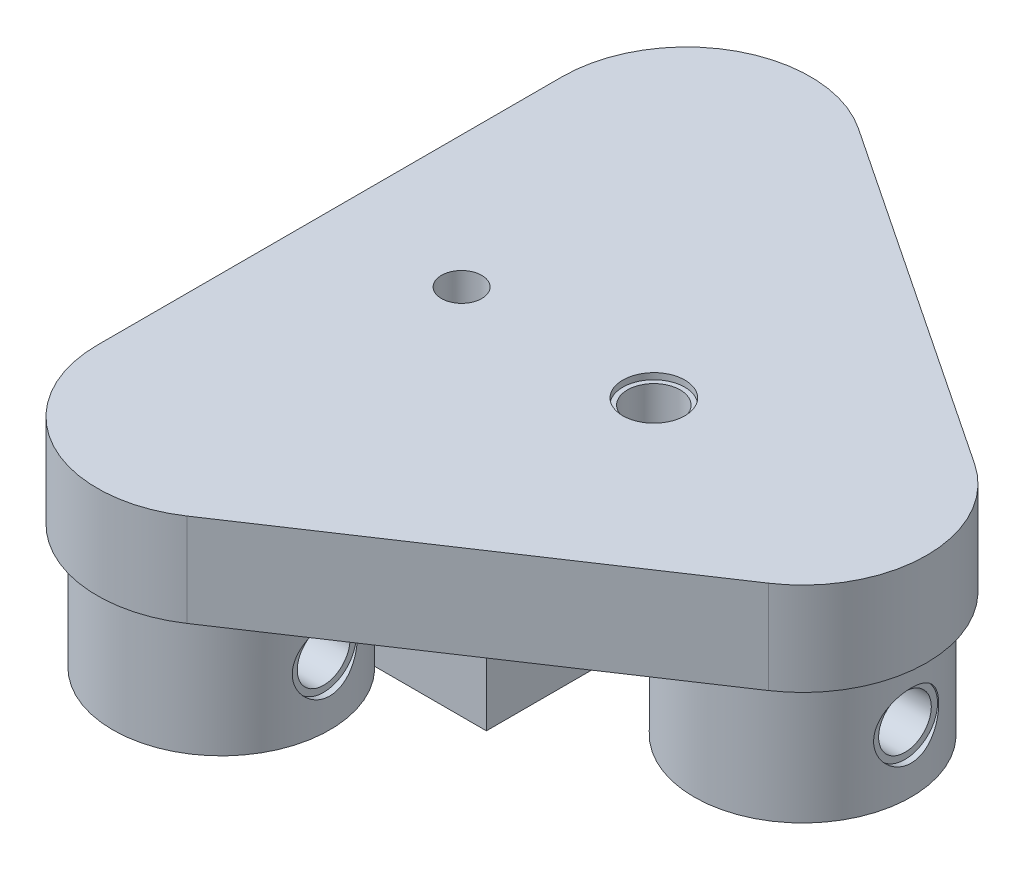
SolidWorks part; units mm, degrees
ref_plane "Front Plane" through (0, 0, 0) normal (0, 0, 1) x (1, 0, 0)
ref_plane "Top Plane" through (0, 0, 0) normal (0, 1, 0) x (1, 0, 0)
ref_plane "Right Plane" through (0, 0, 0) normal (1, 0, 0) x (0, 0, -1)
sketch "Sketch1" plane through (0, 0, 0) normal (0, 1, 0) x (1, 0, 0)
  line L0 (-28.125, 18.75) -> (0, 0) construction
  line L1 (0, 0) -> (-28.125, -18.75) construction
  line L2 (-38.125, 18.75) -> (-38.125, -18.75)
  line L3 (-22.578, -27.0705) -> (5.547, -8.3205)
  line L4 (5.547, 8.3205) -> (-22.578, 27.0705)
  circle A0 centre (0, 0) radius 5 construction
  circle A1 centre (-28.125, 18.75) radius 5 construction
  circle A2 centre (-28.125, -18.75) radius 5 construction
  arc A3 (-22.578, 27.0705) -> (-38.125, 18.75) centre (-28.125, 18.75) ccw
  arc A4 (5.547, -8.3205) -> (5.547, 8.3205) centre (0, 0) ccw
  arc A5 (-38.125, -18.75) -> (-22.578, -27.0705) centre (-28.125, -18.75) ccw
  dimension "D1" = 10
  dimension "D3" = 5
  dimension "D4" = 5
  dimension "D2" = 37.5
  dimension "D5" = 28.125
extrude "Boss-Extrude1" add sketch "Sketch1" along normal blind 7.5
sketch "Sketch3" plane through (0, 0, 0) normal (0, -1, 0) x (1, 0, 0)
  circle A0 centre (-28.125, 18.75) radius 5.125
  circle A1 centre (0, 0) radius 5.125
  circle A2 centre (-28.125, -18.75) radius 5.125
  circle A3 centre (-28.125, 18.75) radius 8.75
  circle A4 centre (-28.125, -18.75) radius 8.75
  circle A5 centre (0, 0) radius 8.75
  dimension "D1" = 10.25
  dimension "D2" = 17.5
sketch "Sketch6" plane through (0, 0, 0) normal (0, -1, 0) x (1, 0, 0)
  line L1 (-18, -7.5) -> (-37, -7.5)
  line L2 (-18, -7.5) -> (-18, 7.5)
  line L3 (-18, 7.5) -> (-37, 7.5)
  line L4 (-37, -7.5) -> (-37, 7.5)
  line L5 (-18, -7.5) -> (-37, 7.5) construction
  line L6 (-18, 7.5) -> (-37, -7.5) construction
  line L7 (-35, -5.5) -> (-35, 5.5)
  line L8 (-20, 5.5) -> (-35, 5.5)
  line L9 (-20, -5.5) -> (-20, 5.5)
  line L10 (-20, -5.5) -> (-35, -5.5)
  point P0 (-27.5, 0)
  dimension "D1" = 27.5
  dimension "D2" = 15
  dimension "D3" = 11
  dimension "D5" = 11
  dimension "D4" = 2
extrude "Boss-Extrude3" add sketch "Sketch6" along normal blind 15
sketch "Sketch7" plane through (0, 0, 0) normal (0, -1, 0) x (1, 0, 0)
  point P0 (-27.5, 0)
hole_wizard "M3 Clearance Hole1" positions "Sketch7" profile "Sketch8" hole size "M3" standard "ANSI Metric" end condition through all
sketch "Sketch8" plane through (-27.5, 0, 0) normal (1, 0, 0) x (0, 0, -1)
  line L0 (0, 0) -> (0, 7.5)
  line L1 (0, 7.5) -> (1.625, 7.5)
  line L2 (1.625, 7.5) -> (1.625, 0)
  line L5 (1.625, 0) -> (0, 0)
  line L11 (0, -6.35) -> (0, 107.95) construction
  dimension "Thru Hole Dia." = 3.25
  dimension "Thru Hole Depth" = 7.5
sketch "Sketch9" plane through (0, 7.5, 0) normal (0, 1, 0) x (1, 0, 0)
  point P0 (-12, 0)
  dimension "D1" = 12
hole_wizard "CBORE for M5 Hex Head Machine Screw1" positions "Sketch9" profile "Sketch10" counterbore size "M5" standard "ANSI Metric" end condition through all
sketch "Sketch10" plane through (-12, 7.5, 0) normal (1, 0, 0) x (0, 0, 1)
  line L0 (0, 0) -> (0, 22.5)
  line L1 (0, 22.5) -> (2.125, 22.5)
  line L3 (2.125, 22.5) -> (2.125, 0.5)
  line L4 (2.125, 0.5) -> (2.5, 0.5)
  line L5 (2.5, 0.5) -> (2.5, 0)
  line L7 (2.5, 0) -> (0, 0)
  line L11 (0, -6.35) -> (0, 107.95) construction
  dimension "Thru Hole Dia." = 4.25
  dimension "Thru Hole Depth" = 22.5
  dimension "C'Bore Dia." = 5
  dimension "C'Bore Depth" = 0.5
extrude "Boss-Extrude4" add sketch "Sketch3" along normal blind 10
ref_plane "Plane1" through (-19.375, 0, 0) normal (1, 0, 0) x (0, 0, -1)
sketch "Sketch11" plane through (-19.375, 0, 0) normal (1, 0, 0) x (0, 0, -1)
  line L0 (-18.75, -10) -> (-18.75, 0) construction
  line L1 (-27.5, -10) -> (-10, -10) construction
  line L2 (-27.0705, 0) -> (-8.3205, 0) construction
  line L3 (18.75, -10) -> (18.75, 0) construction
  line L4 (10, -10) -> (27.5, -10) construction
  line L5 (8.3205, 0) -> (27.0705, 0) construction
  point P12 (18.75, -5)
  point P13 (-18.75, -5)
hole_wizard "CBORE for M3 SHCS1" positions "Sketch11" profile "Sketch12" counterbore size "M3" standard "ANSI Metric"
sketch "Sketch12" plane through (-19.375, -5, 18.75) normal (0, 1, 0) x (0, 0, -1)
  line L0 (0, 0) -> (0, 10)
  line L1 (0, 10) -> (2.125, 10)
  line L2 (2.125, 10) -> (2.125, 0.5)
  line L3 (2.125, 0.5) -> (2.625, 0.5)
  line L4 (2.625, 0.5) -> (2.625, 0)
  line L5 (2.625, 0) -> (0, 0)
  line L10 (0, 10) -> (-2.125, 10) construction
  line L11 (0, -6.35) -> (0, 107.95) construction
  dimension "Hole Dia." = 4.25
  dimension "Hole Depth" = 10
  dimension "C'Bore Dia." = 5.25
  dimension "C'Bore Depth" = 0.5
  dimension "Drill Angle" = 180
ref_plane "Plane2" through (8.75, 0, 0) normal (1, 0, 0) x (0, 0, -1)
sketch "Sketch13" plane through (8.75, 0, 0) normal (1, 0, 0) x (0, 0, -1)
  line L0 (0, -10) -> (0, -3.3568) construction
  line L1 (-8.75, -10) -> (8.75, -10) construction
  point P5 (0, -5)
hole_wizard "CBORE for M3 SHCS2" positions "Sketch13" profile "Sketch14" counterbore size "M3" standard "ANSI Metric"
sketch "Sketch14" plane through (8.75, -5, 0) normal (0, 1, 0) x (0, 0, -1)
  line L0 (0, 0) -> (0, 10)
  line L1 (0, 10) -> (2.125, 10)
  line L2 (2.125, 10) -> (2.125, 0.5)
  line L3 (2.125, 0.5) -> (2.625, 0.5)
  line L4 (2.625, 0.5) -> (2.625, 0)
  line L5 (2.625, 0) -> (0, 0)
  line L10 (0, 10) -> (-2.125, 10) construction
  line L11 (0, -6.35) -> (0, 107.95) construction
  dimension "Hole Dia." = 4.25
  dimension "Hole Depth" = 10
  dimension "C'Bore Dia." = 5.25
  dimension "C'Bore Depth" = 0.5
  dimension "Drill Angle" = 180
sketch "Sketch15" plane through (0, 0, 0) normal (0, -1, 0) x (1, 0, 0)
  circle A0 centre (-28.125, 18.75) radius 5.125
  circle A1 centre (0, 0) radius 5.125
  circle A2 centre (-28.125, -18.75) radius 5.125
  circle A3 centre (-28.125, 18.75) radius 5.125 construction
extrude "Cut-Extrude1" cut sketch "Sketch15" against normal blind 5
